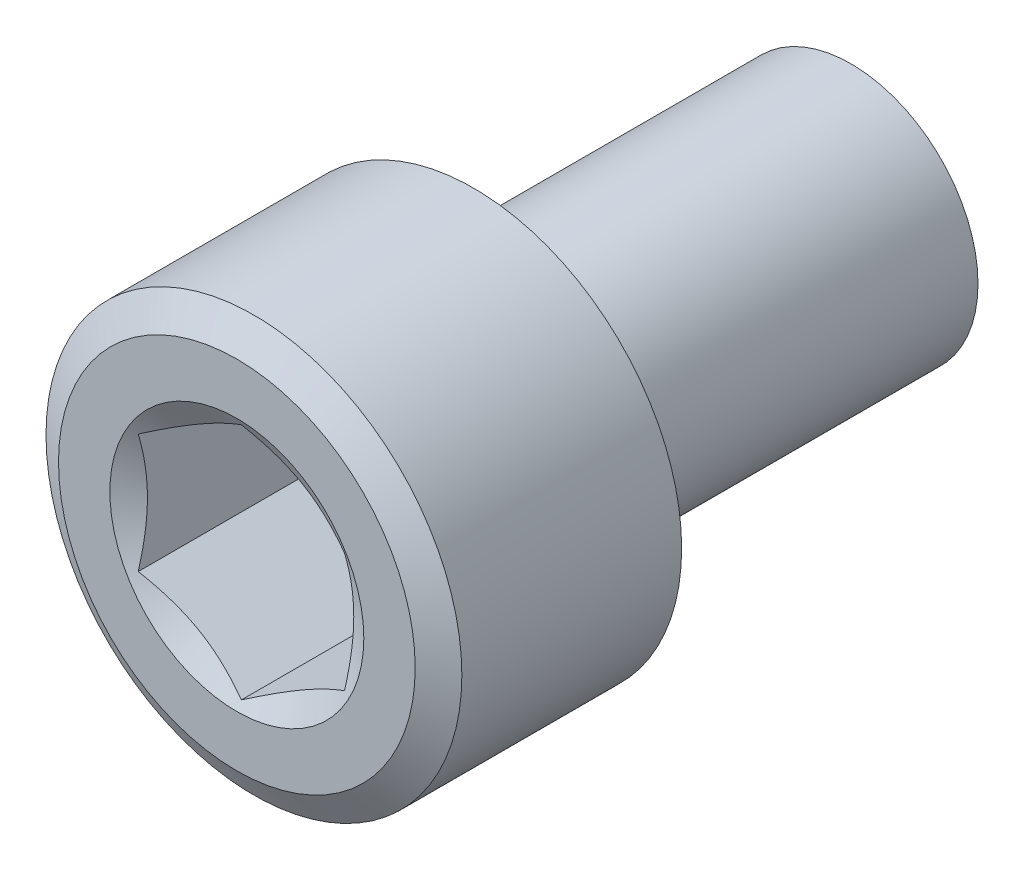
SolidWorks part; units mm, degrees
ref_plane "Front Plane" through (0, 0, 0) normal (0, 0, 1) x (1, 0, 0)
ref_plane "Top Plane" through (0, 0, 0) normal (0, 1, 0) x (1, 0, 0)
ref_plane "Right Plane" through (0, 0, 0) normal (1, 0, 0) x (0, 0, -1)
sketch "Sketch1" plane through (0, 0, 0) normal (1, 0, 0) x (0, 0, -1)
  line L0 (0, 0) -> (38, 0) construction
  line L1 (0, 0) -> (0, 5.6182)
  line L2 (0, 5.6182) -> (0.538, 6.55)
  line L3 (0.538, 6.55) -> (7.462, 6.55)
  line L4 (7.462, 6.55) -> (8, 5.6182)
  line L5 (8, 5.6182) -> (8, 4)
  line L6 (8, 4) -> (38, 4)
  line L7 (38, 4) -> (38, 0)
  line L8 (0, 0) -> (38, 0)
  dimension "D1" = 4
  dimension "D2" = 30
  dimension "D3" = 8
  dimension "D4" = 30
  dimension "D5" = 30
  dimension "D6" = 6.55
  dimension "D7" = 0.538
  dimension "D8" = 0.538
revolve "Revolve1" add sketch "Sketch1" angle 360 about L0
chamfer "Chamfer1" distance 0.8 angle 45 1 edges at (4, 0, -38)
sketch "Sketch2" plane through (0, 0, 0) normal (0, 0, 1) x (1, 0, 0)
  line L1 (3.25, 1.8764) -> (0, 3.7528)
  line L2 (0, 3.7528) -> (-3.25, 1.8764)
  line L3 (-3.25, 1.8764) -> (-3.25, -1.8764)
  line L4 (-3.25, -1.8764) -> (0, -3.7528)
  line L5 (0, -3.7528) -> (3.25, -1.8764)
  line L6 (3.25, -1.8764) -> (3.25, 1.8764)
  circle A0 centre (0, 0) radius 3.25 construction
  dimension "D1" = 6.5
extrude "Cut-Extrude1" cut sketch "Sketch2" against normal blind 6
sketch "Sketch3" plane through (0, 0, 0) normal (1, 0, 0) x (0, 0, -1)
  line L0 (-1.4028, 0) -> (13.9771, 0) construction
  line L1 (0, 0) -> (0, 4)
  line L2 (0, 5.6182) -> (0, -5.6182) construction
  line L3 (0, 4) -> (2.3094, 0)
  line L4 (2.3094, 0) -> (0, 0)
  line L5 (6, 0) -> (6, 3.7528)
  line L6 (6, -1.8764) -> (6, 1.8764) construction
  line L7 (6, 3.7528) -> (8.1667, 0)
  line L8 (8.1667, 0) -> (6, 0)
  dimension "D1" = 30
  dimension "D2" = 30
  dimension "D3" = 4
revolve "Cut-Revolve1" cut sketch "Sketch3" angle 360 about L0
sketch "Sketch4" plane through (0, 0, -38) normal (0, 0, -1) x (-1, 0, 0)
  circle A0 centre (0, 0) radius 4 construction
  circle A1 centre (0, 0) radius 4
sketch "Sketch17" plane through (3.25, 0, 0) normal (-1, 0, 0) x (0, 0, 1)
  line L1 (-38.9715, 6.4979) -> (-29.6796, 6.4979)
  line L2 (-38.9715, 6.4979) -> (-38.9715, -8.3499)
  line L3 (-38.9715, -8.3499) -> (-29.6796, -8.3499)
  line L4 (-29.6796, 6.4979) -> (-29.6796, -8.3499)
extrude "Cut-Extrude2" cut sketch "Sketch17" along normal blind 21 and the other way blind 18
sketch "Sketch18" plane through (1.625, 2.8146, 0) normal (-0.5, -0.866, 0) x (0.866, -0.5, 0)
  line L1 (-7.1338, -24.3792) -> (9.8083, -24.3792)
  line L2 (-7.1338, -24.3792) -> (-7.1338, -30.1229)
  line L3 (-7.1338, -30.1229) -> (9.8083, -30.1229)
  line L4 (9.8083, -24.3792) -> (9.8083, -30.1229)
extrude "Cut-Extrude3" cut sketch "Sketch18" along normal blind 18 and the other way blind 18
sketch "Sketch19" plane through (0, 0, 0) normal (1, 0, 0) x (0, 0, -1)
  line L1 (19.3476, 5.3529) -> (24.5988, 5.3529)
  line L2 (19.3476, 5.3529) -> (19.3476, -5.7279)
  line L3 (19.3476, -5.7279) -> (24.5988, -5.7279)
  line L4 (24.5988, 5.3529) -> (24.5988, -5.7279)
extrude "Cut-Extrude4" cut sketch "Sketch19" along normal blind 36 and the other way blind 60
